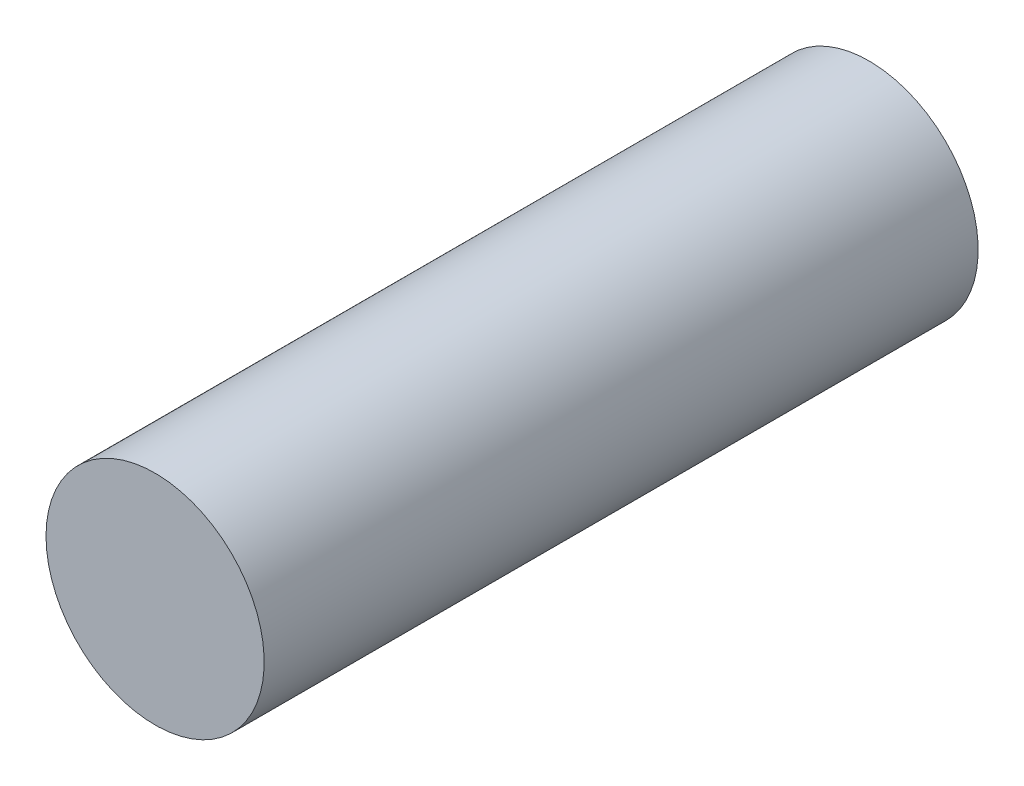
SolidWorks part; units mm, degrees
ref_plane "Front Plane" through (0, 0, 0) normal (1, 0, 0) x (0, 1, 0)
ref_plane "Top Plane" through (0, 0, 0) normal (0, 0, 1) x (0, 1, 0)
ref_plane "Right Plane" through (0, 0, 0) normal (0, 1, 0) x (-1, 0, 0)
sketch "Sketch1" plane through (0, 0, 0) normal (0, 1, 0) x (-1, 0, 0)
  line L0 (-3.8, 0) -> (-5.5, 0)
  line L1 (-5.5, 0) -> (-5.5, 36)
  line L2 (-5.5, 36) -> (0, 36)
  line L3 (0, 36) -> (0, 33)
  line L4 (0, 33) -> (-3.4, 33)
  line L5 (-3.4, 33) -> (-3.4, 0.4)
  line L6 (-3.4, 0.4) -> (-3.8, 0)
  line L7 (0, -200) -> (0, 200) construction
revolve "Bore" add sketch "Sketch1" angle 360 about L7
sketch "Sketch2" plane through (0, 0, 0) normal (0, 1, 0) x (-1, 0, 0)
  line L0 (-3.6, 24.13) -> (-4.4, 24.13)
  line L1 (-4.4, 24.13) -> (-4.4, 27.93)
  line L2 (-4.4, 27.93) -> (-3.6, 27.93)
  line L3 (-3.6, 27.93) -> (-2.35, 24.43)
  line L4 (-2.35, 24.43) -> (-3.6, 24.13)
  line L5 (0, -200) -> (0, 200) construction
revolve "Detent" add sketch "Sketch2" angle 360 about L5
